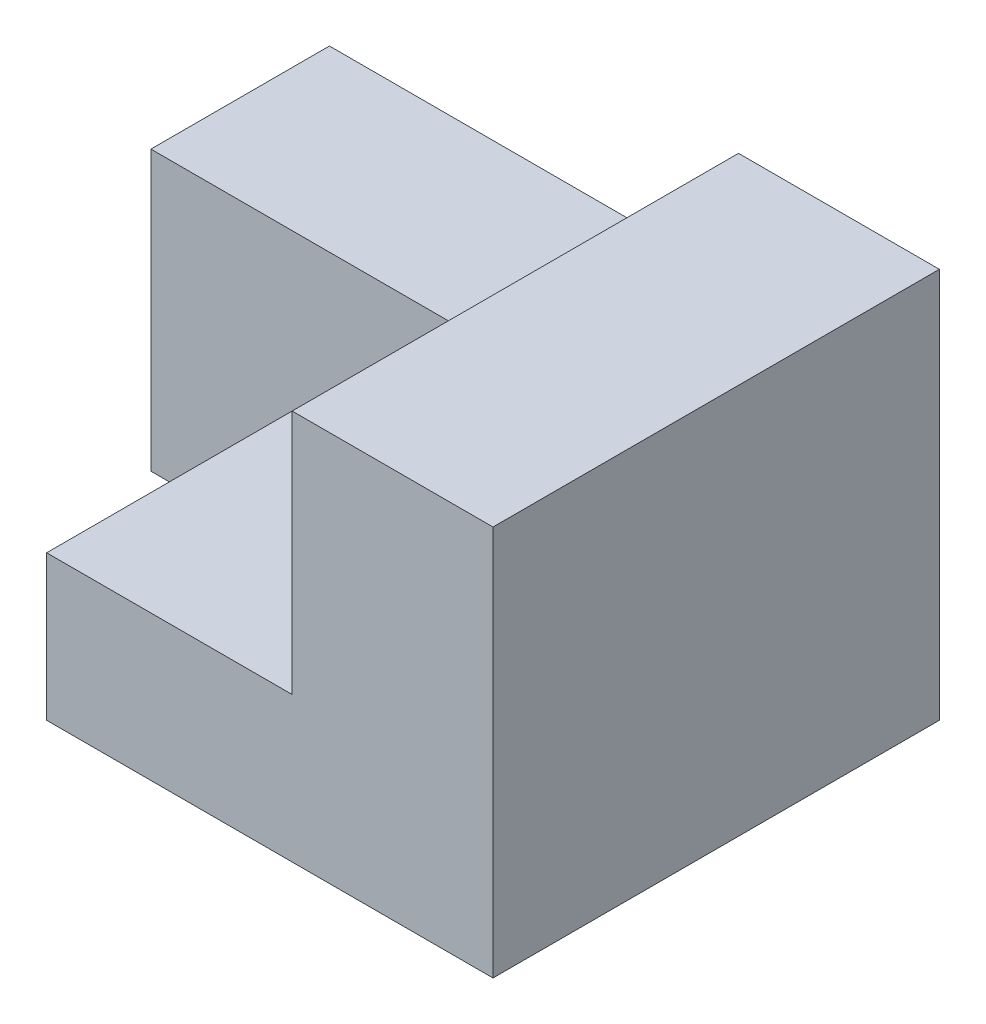
SolidWorks part; units mm, degrees
ref_plane "Front Plane" through (0, 0, 0) normal (0, 0, 1) x (1, 0, 0)
ref_plane "Top Plane" through (0, 0, 0) normal (0, 1, 0) x (1, 0, 0)
ref_plane "Right Plane" through (0, 0, 0) normal (1, 0, 0) x (0, 0, -1)
sketch "Sketch1" plane through (0, 0, 0) normal (0, 0, 1) x (1, 0, 0)
  line L0 (0, 0) -> (0, 35)
  line L1 (0, 35) -> (-18, 35)
  line L2 (-18, 35) -> (-18, 13)
  line L3 (-18, 13) -> (-40, 13)
  line L4 (-40, 13) -> (-40, 0)
  line L5 (-40, 0) -> (0, 0)
  dimension "D1" = 35
  dimension "D2" = 18
  dimension "D3" = 40
  dimension "D4" = 13
extrude "Boss-Extrude1" add sketch "Sketch1" against normal blind 40
sketch "Sketch2" plane through (0, 0, -40) normal (0, 0, -1) x (-1, 0, 0)
  line L0 (18, 13) -> (18, 25)
  line L2 (18, 25) -> (54.6578, 25)
  line L3 (54.6578, 25) -> (54.6578, 0)
  line L4 (54.6578, 0) -> (40, 0)
  line L5 (40, 0) -> (40, 13)
  line L6 (40, 13) -> (18, 13)
  dimension "D1" = 25
extrude "Boss-Extrude2" add sketch "Sketch2" against normal blind 16
